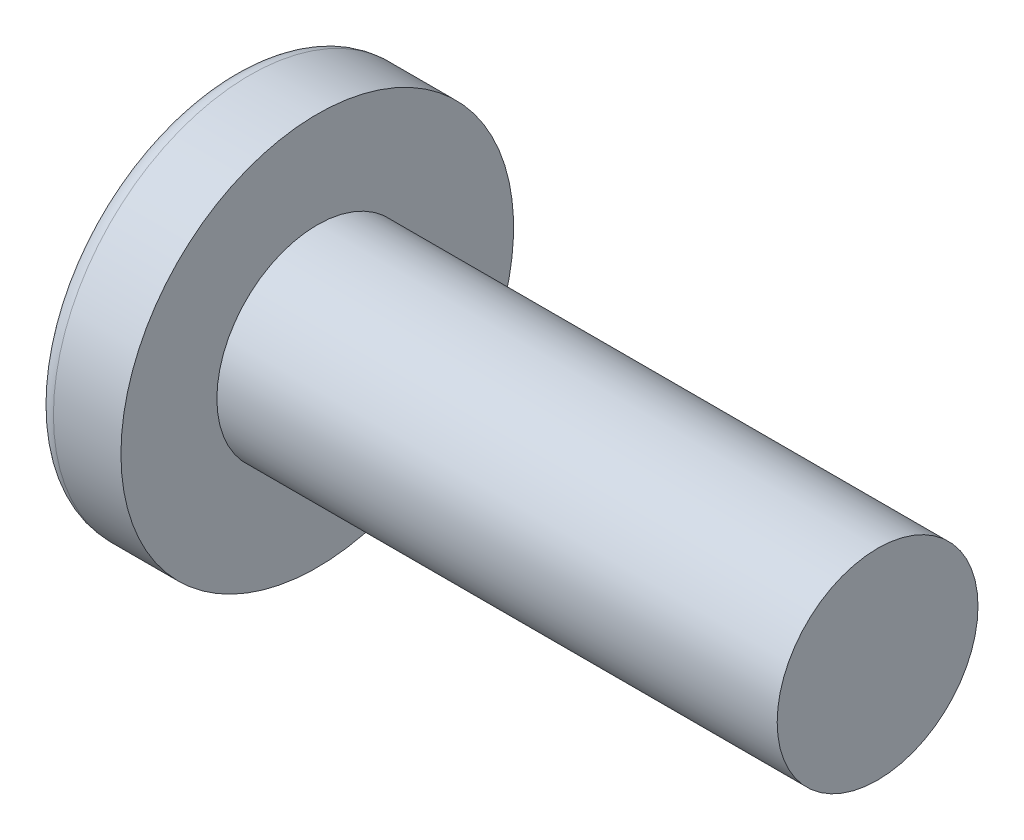
SolidWorks part; units mm, degrees
other "Defeature"
material "Alloy Steel"
ref_plane "Plane1" through (0, 0, 0) normal (0, 0, 1) x (1, 0, 0)
ref_plane "Plane2" through (0, 0, 0) normal (0, 1, 0) x (1, 0, 0)
ref_plane "Plane3" through (0, 0, 0) normal (1, 0, 0) x (0, 0, -1)
sketch "BodySke" plane through (0, 0, 0) normal (0, 0, 1) x (1, 0, 0)
  line L0 (2.032, 1.4224) -> (2.032, 2.7813)
  line L1 (2.3495, 6.35) -> (2.3495, -3.175) construction
  line L2 (-25.4, 0) -> (127, 0) construction
  line L3 (9.9695, 0) -> (0, 0)
  line L4 (2.032, 1.4224) -> (9.9695, 1.4224)
  line L5 (9.9695, 1.4224) -> (9.9695, 0)
  line L6 (1.0756, 2.7813) -> (2.032, 2.7813)
  line L7 (2.032, -1.4224) -> (9.9695, -1.4224) construction
  line L8 (2.032, 6.35) -> (2.032, -3.175) construction
  arc A0 (0.8702, 2.6767) -> (0, 0) centre (4.5517, 0) ccw
  arc A2 (0.8702, 2.6767) -> (1.0756, 2.7813) centre (1.0756, 2.5273) cw
  dimension "Head_fillet_rad" = 0.254
  dimension "Head_crown_rad" = 4.5517
  dimension "Head_ht" = 2.032
  dimension "Diameter" = 2.8448
  dimension "Length" = 7.9375
  dimension "Head_dia" = 5.5626
  dimension "Advance" = 0.635
  dimension "Thread_nom" = 7.9375
revolve "Base-Revolve" add sketch "BodySke" angle 360 about L2
cosmetic thread "ThreadCosmetic" [suppressed] parameters "Thread_length"=7.3025, "Thread_minor"=2.0879
sketch "Sketch3" plane through (0, 0, 0) normal (1, 0, 0) x (0, 0, -1)
  line L0 (0.4064, -1.8161) -> (-0.4064, -1.8161)
  line L1 (0.4064, -1.8161) -> (0.4064, 1.8161)
  line L2 (-0.4064, 1.8161) -> (0.4064, 1.8161)
  line L3 (-0.4064, 1.8161) -> (-0.4064, -1.8161)
  dimension "D1" = 1.8161
  dimension "Cross_dia" = 3.6322
  dimension "D2" = 0.4064
  dimension "Cross_width" = 0.8128
ref_plane "Plane4" through (2.0066, 0, 0) normal (1, 0, 0) x (0, 0, -1)
sketch "Sketch4" plane through (2.0066, 0, 0) normal (1, 0, 0) x (0, 0, -1)
  line L0 (0.2032, -0.2032) -> (-0.2032, -0.2032)
  line L1 (0.2032, -0.2032) -> (0.2032, 0.2032)
  line L2 (-0.2032, 0.2032) -> (0.2032, 0.2032)
  line L3 (-0.2032, 0.2032) -> (-0.2032, -0.2032)
  dimension "D1" = 0.4064
  dimension "D2" = 0.4064
  dimension "D3" = 0.2032
  dimension "D4" = 0.2032
loft "Cut-Loft1" cut profiles "Sketch3", "Sketch4"
pattern_circular "CirPattern1" count 2 every 90 about axis through (0, 0, 0) along (1, 0, 0) of "Cut-Loft1"
sketch "ThdSchSke" plane through (0, 0, 0) normal (0, 0, 1) x (1, 0, 0)
  line L0 (2.667, -1.0439) -> (2.402, -1.4224)
  line L1 (2.667, -1.0439) -> (2.932, -1.4224)
  line L2 (2.932, -1.4224) -> (2.932, -1.778)
  line L3 (-3.175, 0) -> (5.1513, 0) construction
  line L5 (2.932, -1.778) -> (2.402, -1.778)
  line L6 (2.402, -1.778) -> (2.402, -1.4224)
  dimension "Thread_minor" = 2.0879
  dimension "Diameter" = 2.8448
  dimension "Start" = 2.667
  dimension "SideAngle" = 55
  dimension "VeeAngle" = 70
  dimension "Overcut" = 3.556
revolve "ThreadSchematic" [suppressed] cut sketch "ThdSchSke" angle 360 about L3
pattern_linear "ThdSchPat" [suppressed]
equation "\"D1@Sketch3\" = \"Cross_dia@Sketch3\" / 2"
equation "\"D2@Sketch3\" = \"Cross_width@Sketch3\" / 2"
equation "\"D1@Sketch4\" = \"Cross_width@Sketch3\" *.5"
equation "\"D2@Sketch4\" = \"D1@Sketch4\""
equation "\"D3@Sketch4\" = \"D1@Sketch4\" / 2"
equation "\"D4@Sketch4\" = \"D2@Sketch4\" / 2"
equation "\"Thread_length@ThreadCosmetic\" = ((sgn( (\"Length@BodySke\" - \"Advance@BodySke\" ) - \"Thread_nom@BodySke\" )-1)*( (\"Length@BodySke\" - \"Advance@BodySke\" ) - \"Thread_nom@BodySke\" ))/-2+ \"Thread_nom@BodySke\""
equation "\"Thread_minor@ThdSchSke\" = \"Thread_minor@ThreadCosmetic\""
equation "\"Diameter@ThdSchSke\" = \"Diameter@BodySke\""
equation "\"Overcut@ThdSchSke\" = \"Diameter@BodySke\" * 1.25"
equation "\"Start@ThdSchSke\" = \"Head_ht@BodySke\" + \"Length@BodySke\" - \"Thread_length@ThreadCosmetic\"  '---Non-countersunk---"
equation "\"Num_threads@ThdSchPat\" = int( \"Thread_length@ThreadCosmetic\" / \"Advance@BodySke\" + 0.999 )  + 1"
equation "\"Advance@ThdSchPat\" = \"Thread_length@ThreadCosmetic\" /  (\"Num_threads@ThdSchPat\" - 1) 'relax it"
